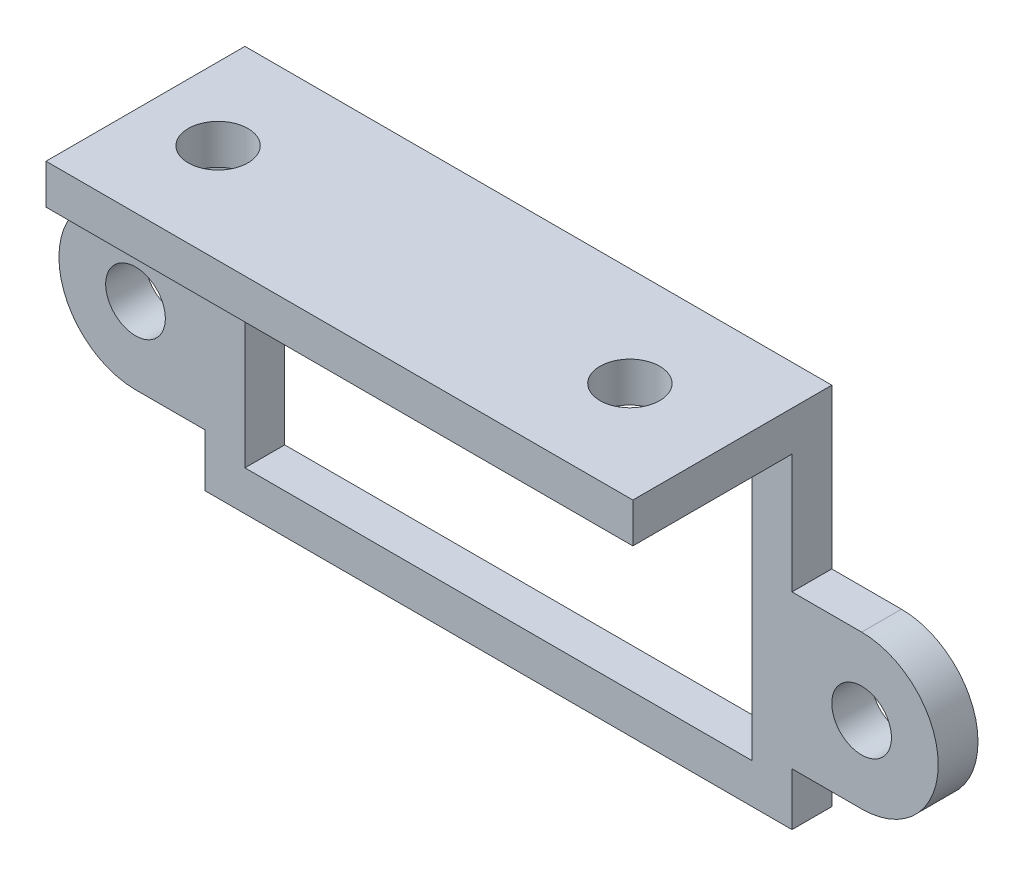
SolidWorks part; units mm, degrees
ref_plane "Front Plane" through (0, 0, 0) normal (0, 0, 1) x (1, 0, 0)
ref_plane "Top Plane" through (0, 0, 0) normal (0, 1, 0) x (1, 0, 0)
ref_plane "Right Plane" through (0, 0, 0) normal (1, 0, 0) x (0, 0, -1)
sketch "Sketch1" plane through (0, 0, 0) normal (0, 0, 1) x (1, 0, 0)
  line L0 (0, 18.35) -> (0, 10.35)
  line L1 (0, 0) -> (29.5, 0)
  line L2 (0, 2.65) -> (0, 0)
  line L3 (0, 18.35) -> (29.5, 18.35)
  line L4 (29.5, 18.35) -> (29.5, 10.35)
  line L5 (0, 10.35) -> (-3.5, 10.35)
  line L6 (-2, 6.5) -> (-2, 3.6258) construction
  line L7 (0, 2.65) -> (-3.5, 2.65)
  line L8 (14.75, 18.35) -> (14.75, 0) construction
  line L9 (29.5, 10.35) -> (33, 10.35)
  line L10 (29.5, 2.65) -> (33, 2.65)
  line L11 (29.5, 2.65) -> (29.5, 0)
  line L13 (2, 2) -> (27.5, 2)
  line L14 (2, 2) -> (2, 16.35)
  line L15 (2, 16.35) -> (27.5, 16.35)
  line L16 (27.5, 2) -> (27.5, 16.35)
  arc A0 (-3.5, 10.35) -> (-3.5, 2.65) centre (-3.5, 6.5) ccw
  circle A1 centre (-3.5, 6.5) radius 1.5
  arc A2 (33, 10.35) -> (33, 2.65) centre (33, 6.5) cw
  circle A3 centre (33, 6.5) radius 1.5
  dimension "D5" = 3
  dimension "D1" = 14.75
  dimension "D2" = 2.65
  dimension "D3" = 7.7
  dimension "D4" = 2
  dimension "D6" = 8
  dimension "D7" = 2
  dimension "D8" = 2
  dimension "D9" = 2
  dimension "D10" = 2
extrude "Boss-Extrude1" add sketch "Sketch1" along normal blind 2
sketch "Sketch2" plane through (0, 0, 2) normal (0, 0, 1) x (1, 0, 0)
  line L0 (29.5, 10.35) -> (29.5, 18.35) construction
  line L1 (0, 18.35) -> (29.5, 18.35)
  line L2 (0, 18.35) -> (0, 16.35)
  line L3 (0, 16.35) -> (29.5, 16.35)
  line L4 (29.5, 18.35) -> (29.5, 16.35)
  dimension "D1" = 2
extrude "Boss-Extrude2" add sketch "Sketch2" along normal blind 8
sketch "Sketch3" plane through (0, 18.35, 0) normal (0, 1, 0) x (1, 0, 0)
  line L0 (3.65, -5) -> (24.35, -5) construction
  line L1 (22.85, -3.5) -> (22.85, -6.5) construction
  line L2 (5.15, -3.5) -> (5.15, -6.5) construction
  line L3 (3.65, -5) -> (0, -5) construction
  line L4 (0, -10) -> (0, 0) construction
  line L5 (0, -5) -> (2.15, -5) construction
  line L6 (25.85, -5) -> (29.5, -5) construction
  line L7 (29.5, -10) -> (29.5, 0) construction
  circle A0 centre (3.65, -5) radius 1.5
  circle A1 centre (24.35, -5) radius 1.5
  dimension "D1" = 3
  dimension "D2" = 17.7
extrude "Cut-Extrude1" cut sketch "Sketch3" against normal blind 8
